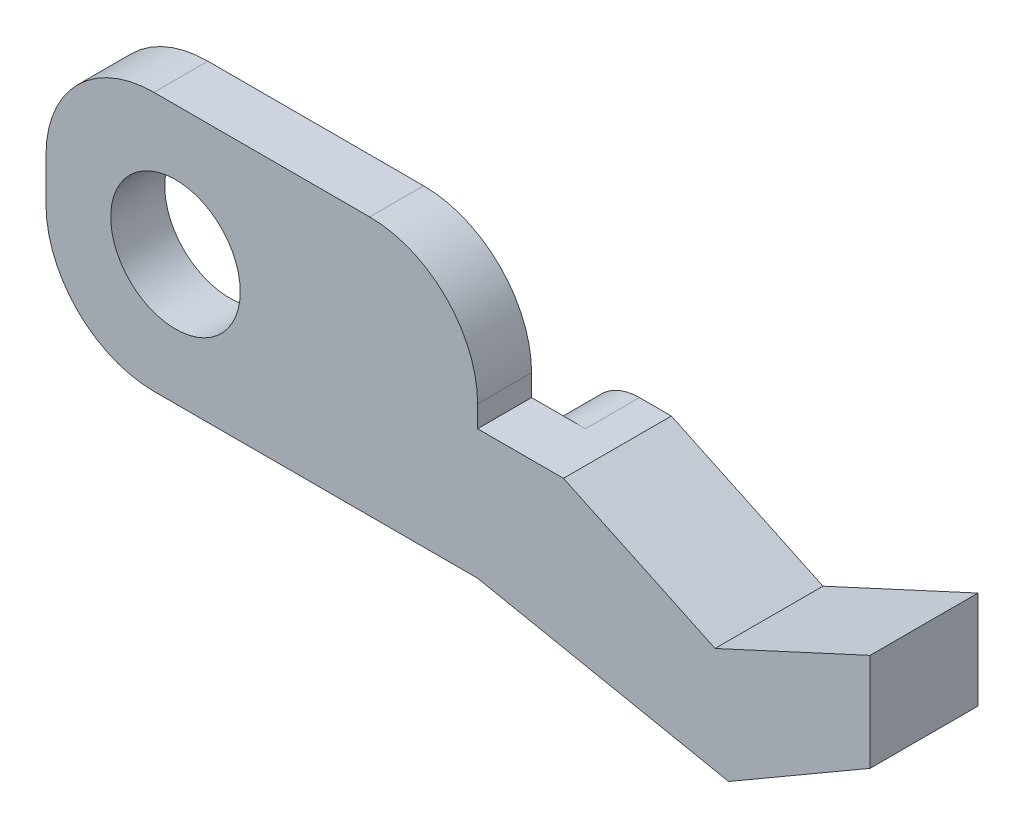
SolidWorks part; units mm, degrees
ref_plane "Ön Düzlem" through (0, 0, 0) normal (0, 0, 1) x (1, 0, 0)
ref_plane "Üst Düzlem" through (0, 0, 0) normal (0, 1, 0) x (1, 0, 0)
ref_plane "Sağ Düzlem" through (0, 0, 0) normal (1, 0, 0) x (0, 0, -1)
sketch "Sketch1" plane through (0, 0, 0) normal (1, 0, 0) x (0, 0, -1)
  circle A0 centre (0, 0) radius 6
extrude "Boss-Extrude1" add sketch "Sketch1" along normal blind 20
sketch "Sketch3" plane through (0, 0, 0) normal (-1, 0, 0) x (0, 0, 1)
  line L5 (2.5, 7.3201) -> (6.8351, 7.3201)
  line L6 (2.5, 7.3201) -> (2.5, -6.7386)
  line L7 (2.5, -6.7386) -> (6.8351, -6.7386)
  line L8 (6.8351, 7.3201) -> (6.8351, -6.7386)
  dimension "D2" = 2.5
extrude "Cut-Extrude1" cut sketch "Sketch3" against normal blind 38
sketch "Sketch4" plane through (0, 0, 2.5) normal (0, 0, 1) x (1, 0, 0)
  circle A0 centre (5, 0) radius 3
extrude "Cut-Extrude2" cut sketch "Sketch4" against normal blind 8
sketch "Sketch5" plane through (0, 0, 0) normal (1, 0, 0) x (0, 0, -1)
  line L1 (9.3831, 6.9556) -> (2.5, 6.9556)
  line L2 (9.3831, 6.9556) -> (9.3831, -7.7164)
  line L3 (9.3831, -7.7164) -> (2.5, -7.7164)
  line L4 (2.5, 6.9556) -> (2.5, -7.7164)
  dimension "D1" = 2.5
extrude "Cut-Extrude3" cut sketch "Sketch5" along normal blind 40
sketch "Sketch7" plane through (0, 0, 0) normal (0, 0, 1) x (1, 0, 0)
  line L0 (20, 0) -> (20, -6)
  line L1 (20, -5.4544) -> (20, 5.4544) construction
  line L2 (20, -6) -> (20, -5.4544) construction
  line L3 (20, -6) -> (31.6312, -8.3407)
  line L4 (31.6312, -8.3407) -> (38.1874, -4.5358)
  line L5 (38.1874, -4.5358) -> (38.1874, 0)
  line L6 (20, 0) -> (23.9784, 0)
  line L8 (31.0045, -3.3149) -> (38.1874, 0)
  line L9 (23.9784, 0) -> (31.0045, -3.3149)
extrude "Boss-Extrude3" add sketch "Sketch7" along normal mid plane 5
sketch "Sketch8" plane through (0, 0, 0) normal (0, 1, 0) x (1, 0, 0)
  line L1 (-0.9186, 4.0628) -> (20, 4.0628)
  line L2 (-0.9186, 4.0628) -> (-0.9186, 0)
  line L3 (-0.9186, 0) -> (20, 0)
  line L4 (20, 4.0628) -> (20, 0)
  line L5 (0, -2.5) -> (20, -2.5) construction
  dimension "D1" = 2.5
extrude "Cut-Extrude4" cut sketch "Sketch8" against normal mid plane 25
sketch "Sketch9" plane through (0, 0, 2.5) normal (0, 0, 1) x (1, 0, 0)
  line L1 (0, -6) -> (20, -6)
  line L2 (0, -6) -> (0, 6)
  line L3 (0, 6) -> (20, 6)
  line L4 (20, -6) -> (20, 6)
extrude "Boss-Extrude4" add sketch "Sketch9" against normal blind 2.5
fillet "Fillet1" radius 5 3 edges at (0, -6, 1.25) (0, 6, 1.25) (20, 6, 1.25)
sketch "Sketch10" plane through (0, 0, 2.5) normal (0, 0, 1) x (1, 0, 0)
  circle A0 centre (6, 0) radius 3
extrude "Cut-Extrude5" cut sketch "Sketch10" against normal blind 6.5
fillet "Fillet2" radius 2.5 2 edges at (20, -6, -1.25)
